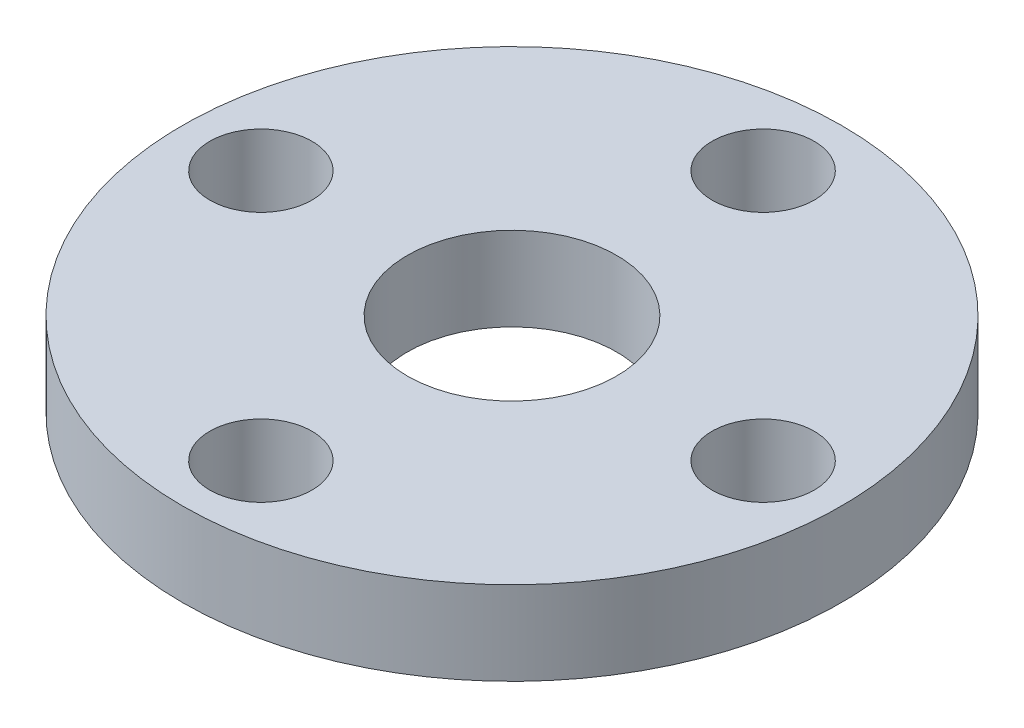
SolidWorks part; units mm, degrees
ref_plane "Front Plane" through (0, 0, 0) normal (0, 0, 1) x (1, 0, 0)
ref_plane "Top Plane" through (0, 0, 0) normal (0, 1, 0) x (1, 0, 0)
ref_plane "Right Plane" through (0, 0, 0) normal (1, 0, 0) x (0, 0, -1)
sketch "Sketch1" plane through (0, 0, 0) normal (0, 1, 0) x (1, 0, 0)
  line L0 (0, 10) -> (0, 3.175) construction
  circle A0 centre (0, 0) radius 10
  circle A1 centre (0, 0) radius 3.175
  circle A3 centre (0, 0) radius 7.62 construction
  circle A4 centre (0, 7.62) radius 1.55
  circle A5 centre (7.62, 0) radius 1.55
  circle A6 centre (0, -7.62) radius 1.55
  circle A7 centre (-7.62, 0) radius 1.55
  point P7 (0, 3.175)
  point P9 (0, 7.62)
  point P20 (0, 0)
  dimension "D1" = 20
  dimension "D2" = 6.35
  dimension "D3" = 3.1
  dimension "D5" = 15.24
  dimension "D4" = 4
extrude "Boss-Extrude1" add sketch "Sketch1" along normal blind 2.54
